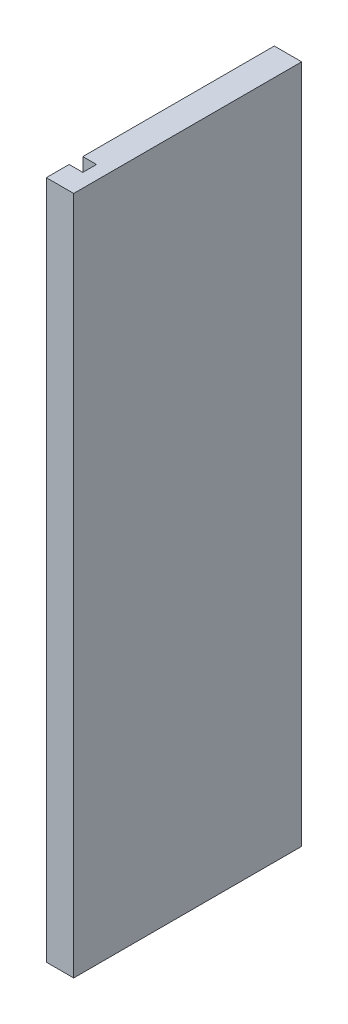
SolidWorks part; units mm, degrees
ref_plane "Alzado" through (0, 0, 0) normal (0, 0, 1) x (1, 0, 0)
ref_plane "Planta" through (0, 0, 0) normal (0, 1, 0) x (1, 0, 0)
ref_plane "Vista lateral" through (0, 0, 0) normal (1, 0, 0) x (0, 0, -1)
sketch "Croquis1" plane through (0, 0, 0) normal (0, 1, 0) x (1, 0, 0)
  line L0 (12, 24.2448) -> (12, -75.7552)
  line L1 (12, -75.7552) -> (0, -75.7552)
  line L2 (0, -75.7552) -> (0, -65.7552)
  line L3 (0, -65.7552) -> (6, -65.7552)
  line L4 (6, -65.7552) -> (6, -59.7552)
  line L5 (6, -59.7552) -> (0, -59.7552)
  line L6 (0, -59.7552) -> (0, 24.2448)
  line L7 (0, 24.2448) -> (12, 24.2448)
  point P2 (0, 0)
  dimension "D1" = 12
  dimension "D2" = 12
  dimension "D3" = 6
  dimension "D4" = 6
  dimension "D5" = 10
  dimension "D6" = 100
extrude "Saliente-Extruir1" add sketch "Croquis1" along normal blind 298
